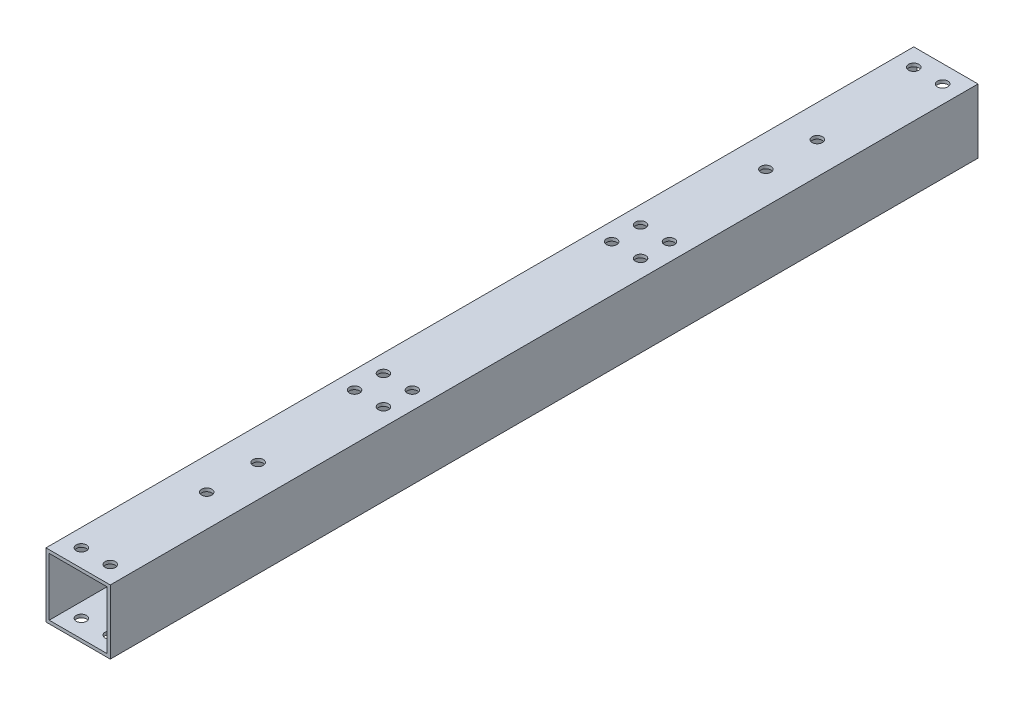
SolidWorks part; units mm, degrees
material "6061-T6 (SS)"
ref_plane "前视基准面" through (0, 0, 0) normal (0, 0, 1) x (1, 0, 0)
ref_plane "上视基准面" through (0, 0, 0) normal (0, 1, 0) x (1, 0, 0)
ref_plane "右视基准面" through (0, 0, 0) normal (1, 0, 0) x (0, 0, -1)
sketch "草图1" plane through (0, 0, 0) normal (0, 0, 1) x (1, 0, 0)
  line L1 (-10, 10) -> (10, 10)
  line L2 (-10, 10) -> (-10, -10)
  line L3 (-10, -10) -> (10, -10)
  line L4 (10, 10) -> (10, -10)
  line L5 (-10, 10) -> (10, -10) construction
  line L6 (-10, -10) -> (10, 10) construction
  line L7 (-9, 9) -> (9, 9)
  line L8 (-9, 9) -> (-9, -9)
  line L9 (-9, -9) -> (9, -9)
  line L10 (9, 9) -> (9, -9)
  line L11 (-9, 9) -> (9, -9) construction
  line L12 (-9, -9) -> (9, 9) construction
  point P0 (0, 0)
  point P6 (0, 0)
  dimension "D1" = 20
  dimension "D2" = 20
  dimension "D3" = 18
  dimension "D4" = 18
extrude "凸台-拉伸1" add sketch "草图1" along normal blind 270
sketch "草图2" plane through (0, 10, 0) normal (0, 1, 0) x (1, 0, 0)
  line L0 (0, -135) -> (78.9073, -135) construction
  line L1 (-10, 0) -> (10, 0) construction
  line L2 (-10, 0) -> (-10, -270) construction
  line L3 (-10, -270) -> (10, -270) construction
  line L4 (10, 0) -> (10, -270) construction
  line L5 (-10, 0) -> (10, -270) construction
  line L6 (-10, -270) -> (10, 0) construction
  line L7 (-10, -105) -> (10, -105) construction
  line L8 (-10, -105) -> (-10, -165) construction
  line L9 (-10, -165) -> (10, -165) construction
  line L10 (10, -105) -> (10, -165) construction
  line L11 (-10, -105) -> (10, -165) construction
  line L12 (-10, -165) -> (10, -105) construction
  line L13 (-10, -165) -> (10, -165) construction
  line L14 (-10, -165) -> (-10, -185) construction
  line L15 (-10, -185) -> (10, -185) construction
  line L16 (10, -165) -> (10, -185) construction
  line L17 (-10, -165) -> (10, -185) construction
  line L18 (-10, -185) -> (10, -165) construction
  line L20 (-4.5, -170.5) -> (4.5, -170.5) construction
  line L21 (-4.5, -170.5) -> (-4.5, -179.5) construction
  line L22 (-4.5, -179.5) -> (4.5, -179.5) construction
  line L23 (4.5, -170.5) -> (4.5, -179.5) construction
  line L24 (-4.5, -170.5) -> (4.5, -179.5) construction
  line L25 (-4.5, -179.5) -> (4.5, -170.5) construction
  circle A0 centre (-4.5, -179.5) radius 1.6
  circle A1 centre (4.5, -179.5) radius 1.6
  circle A2 centre (4.5, -170.5) radius 1.6
  circle A3 centre (-4.5, -170.5) radius 1.6
  circle A4 centre (-4.5, -99.5) radius 1.6
  circle A5 centre (4.5, -90.5) radius 1.6
  circle A6 centre (4.5, -99.5) radius 1.6
  circle A7 centre (-4.5, -90.5) radius 1.6
  point P4 (0, -135)
  point P7 (0, -135)
  point P14 (0, -175)
  point P16 (0, -175)
  dimension "D5" = 2
  dimension "D1" = 60
  dimension "D2" = 20
  dimension "D3" = 9
  dimension "D4" = 9
  dimension "D6" = 2
extrude "切除-拉伸1" cut sketch "草图2" against normal through all
sketch "草图3" plane through (0, -10, 0) normal (0, -1, 0) x (1, 0, 0)
  line L0 (-9, 184) -> (-9, 166)
  line L1 (-4.5, 90.5) -> (4.5, 90.5) construction
  line L2 (-4.5, 90.5) -> (-4.5, 99.5) construction
  line L3 (-4.5, 99.5) -> (4.5, 99.5) construction
  line L4 (4.5, 90.5) -> (4.5, 99.5) construction
  line L5 (-4.5, 90.5) -> (4.5, 99.5) construction
  line L6 (-4.5, 99.5) -> (4.5, 90.5) construction
  line L7 (-9, 104) -> (9, 104)
  line L8 (-9, 104) -> (-9, 86)
  line L9 (-9, 86) -> (9, 86)
  line L10 (9, 104) -> (9, 86)
  line L11 (-9, 104) -> (9, 86) construction
  line L12 (-9, 86) -> (9, 104) construction
  line L13 (-9, 184) -> (9, 184)
  line L14 (9, 184) -> (9, 166)
  line L15 (-9, 166) -> (9, 166)
  point P4 (0, 95)
  point P7 (0, 95)
  dimension "D1" = 18
  dimension "D2" = 18
  dimension "D3" = 2
extrude "切除-拉伸2" cut sketch "草图3" against normal up to next
sketch "草图4" plane through (0, 10, 0) normal (0, 1, 0) x (1, 0, 0)
  line L0 (-10, -270) -> (-10, 0) construction
  line L1 (-10, 0) -> (10, 0) construction
  line L2 (-10, 0) -> (-10, -20) construction
  line L3 (-10, -20) -> (10, -20) construction
  line L4 (10, 0) -> (10, -20) construction
  line L5 (-10, 0) -> (10, -20) construction
  line L6 (-10, -20) -> (10, 0) construction
  line L7 (10, -270) -> (10, 0) construction
  line L9 (-4.5, -5.5) -> (4.5, -5.5) construction
  line L10 (-4.5, -5.5) -> (-4.5, -14.5) construction
  line L11 (-4.5, -14.5) -> (4.5, -14.5) construction
  line L12 (4.5, -5.5) -> (4.5, -14.5) construction
  line L13 (0, -14.5) -> (0, -5.5) construction
  line L14 (-4.5, -10) -> (4.5, -10) construction
  line L15 (-10, -270) -> (10, -270) construction
  line L16 (-10, -270) -> (-10, -250) construction
  line L17 (-10, -250) -> (10, -250) construction
  line L18 (10, -270) -> (10, -250) construction
  line L19 (-10, -270) -> (10, -250) construction
  line L20 (-10, -250) -> (10, -270) construction
  line L21 (-4.5, -255.5) -> (4.5, -255.5) construction
  line L22 (-4.5, -255.5) -> (-4.5, -264.5) construction
  line L23 (-4.5, -264.5) -> (4.5, -264.5) construction
  line L24 (4.5, -255.5) -> (4.5, -264.5) construction
  line L25 (0, -264.5) -> (0, -255.5) construction
  line L26 (-4.5, -260) -> (4.5, -260) construction
  circle A0 centre (-4.5, -5.5) radius 1.6
  circle A1 centre (4.5, -5.5) radius 1.6
  circle A2 centre (-4.5, -264.5) radius 1.6
  circle A3 centre (4.5, -264.5) radius 1.6
  point P4 (0, -10)
  point P9 (0, -10)
  point P19 (0, -260)
  point P20 (0, -260)
  dimension "D4" = 20
  dimension "D1" = 20
  dimension "D2" = 9
  dimension "D3" = 9
  dimension "D5" = 9
  dimension "D6" = 9
extrude "切除-拉伸3" cut sketch "草图4" against normal through all
sketch "草图5" plane through (0, -10, 0) normal (0, -1, 0) x (1, 0, 0)
  line L0 (10, 270) -> (10, 0) construction
  line L1 (-10, 0) -> (10, 0) construction
  line L2 (-10, 0) -> (-10, 40) construction
  line L3 (-10, 40) -> (10, 40) construction
  line L4 (10, 0) -> (10, 40) construction
  line L5 (0, 40) -> (0, 0) construction
  line L6 (-10, 20) -> (10, 20) construction
  line L8 (-10, 40) -> (10, 40) construction
  line L9 (-10, 40) -> (-10, 56) construction
  line L10 (-10, 56) -> (10, 56) construction
  line L11 (10, 40) -> (10, 56) construction
  line L12 (0, 56) -> (0, 40) construction
  line L13 (-10, 48) -> (10, 48) construction
  circle A0 centre (0, 56) radius 1.6
  circle A1 centre (0, 40) radius 1.6
  point P220 (0, 48)
  point P256 (0, 20)
  dimension "D1" = 40
  dimension "D2" = 16
extrude "切除-拉伸4" cut sketch "草图5" against normal through all
ref_plane "基准面1" through (0, 0, 135) normal (0, 0, -1) x (-1, 0, 0)
mirror "镜向1" about plane through (0, 0, 135) normal (0, 0, -1) of "切除-拉伸4"
